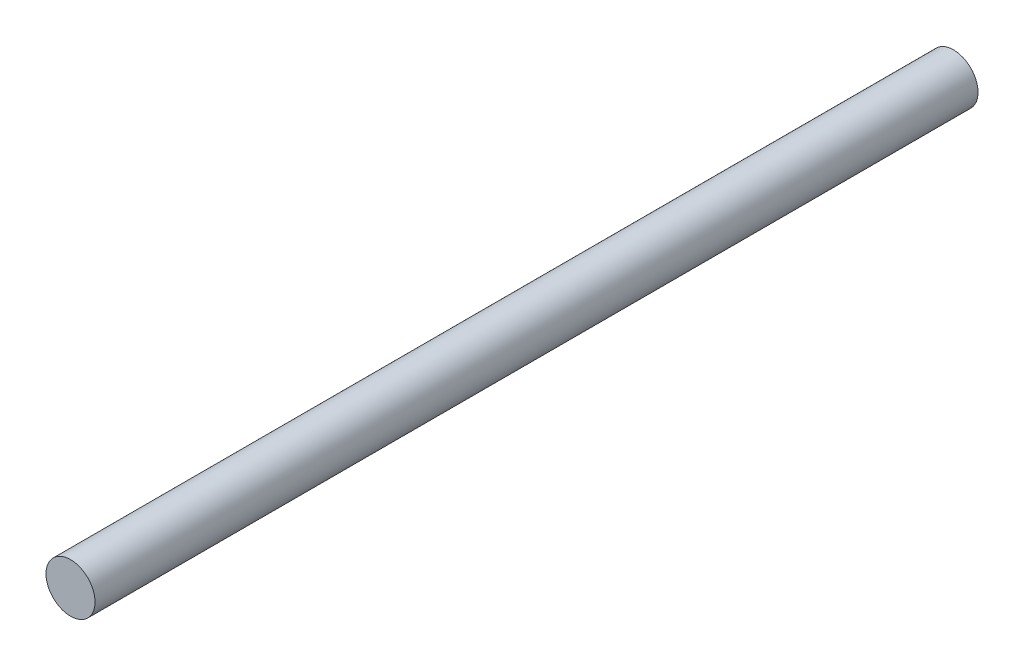
SolidWorks part; units mm, degrees
ref_plane "Plan de face" through (0, 0, 0) normal (0, 0, 1) x (1, 0, 0)
ref_plane "Plan de dessus" through (0, 0, 0) normal (0, 1, 0) x (1, 0, 0)
ref_plane "Plan de droite" through (0, 0, 0) normal (1, 0, 0) x (0, 0, -1)
sketch "Esquisse1" plane through (0, 0, 0) normal (0, 0, 1) x (1, 0, 0)
  circle A0 centre (0, 0) radius 5
  dimension "D1" = 10
extrude "Boss.-Extru.1" add sketch "Esquisse1" along normal blind 180
